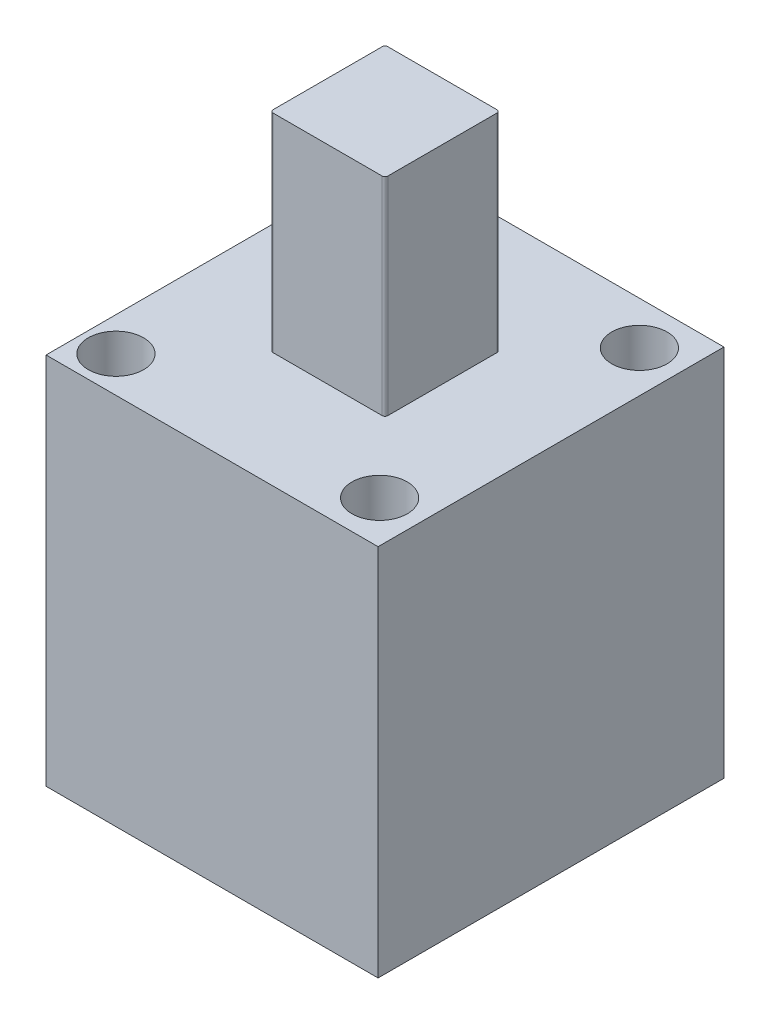
SolidWorks part; units mm, degrees
ref_plane "Alzado" through (0, 0, 0) normal (0, 0, 1) x (1, 0, 0)
ref_plane "Planta" through (0, 0, 0) normal (0, 1, 0) x (1, 0, 0)
ref_plane "Vista lateral" through (0, 0, 0) normal (1, 0, 0) x (0, 0, -1)
sketch "Croquis1" plane through (0, 0, 0) normal (0, 0, 1) x (1, 0, 0)
  line L1 (-49, 13.9228) -> (-25, 13.9228)
  line L2 (-49, 13.9228) -> (-49, -13.0772)
  line L3 (-49, -13.0772) -> (-25, -13.0772)
  line L4 (-25, 13.9228) -> (-25, -13.0772)
  dimension "D1" = 24
  dimension "D2" = 27
extrude "Saliente-Extruir1" add sketch "Croquis1" along normal blind 25
sketch "Croquis2" plane through (0, 13.9228, 0) normal (0, 1, 0) x (1, 0, 0)
  line L0 (-49, 0) -> (-41.15, -8.35) construction
  line L1 (-40.95, -8.35) -> (-33.05, -8.35)
  line L2 (-41.15, -8.55) -> (-41.15, -16.45)
  line L3 (-40.95, -16.65) -> (-33.05, -16.65)
  line L4 (-32.85, -8.55) -> (-32.85, -16.45)
  line L5 (-33.1039, -16.8961) -> (-25, -25) construction
  line L6 (-25, -25) -> (-25, 0) construction
  line L7 (-25, 0) -> (-32.85, -8.35) construction
  line L8 (-41.15, -16.65) -> (-49, -25) construction
  line L11 (-49.9948, -18.9259) -> (-49.9948, -21.9259)
  line L16 (-46.9923, -24.9618) -> (-43.9923, -24.9618)
  circle A0 centre (-45.0661, -4.1845) radius 2
  circle A1 centre (-28.9339, -4.1845) radius 2
  circle A2 centre (-45.0661, -20.8155) radius 2
  circle A3 centre (-28.9233, -21.0767) radius 2
  circle A4 centre (-14.9438, 10.6967) radius 0.6772
  arc A5 (-33.05, -16.65) -> (-32.85, -16.45) centre (-33.05, -16.45) ccw
  arc A6 (-41.15, -16.45) -> (-40.95, -16.65) centre (-40.95, -16.45) ccw
  arc A7 (-33.05, -8.35) -> (-32.85, -8.55) centre (-33.05, -8.55) cw
  arc A8 (-40.95, -8.35) -> (-41.15, -8.55) centre (-40.95, -8.55) ccw
  point P35 (-32.9086, -16.5914)
  dimension "D3" = 0.2
  dimension "D5" = 6
  dimension "D6" = 6
  dimension "D7" = 6
  dimension "D1" = 8.3
  dimension "D2" = 8.3
  dimension "D4" = 6
sketch "Croquis4" plane through (0, 0, 0) normal (0, 0, 1) x (1, 0, 0)
  line L0 (-50, 0) -> (-40.815, -9.185) construction
  line L1 (-40.615, -9.185) -> (-34.385, -9.185)
  line L2 (-40.815, -9.385) -> (-40.815, -15.615)
  line L3 (-40.615, -15.815) -> (-34.385, -15.815)
  line L4 (-34.185, -9.385) -> (-34.185, -15.615)
  line L5 (-34.185, -15.815) -> (-25, -25) construction
  line L6 (-25, -25) -> (-25, 0) construction
  line L7 (-25, 0) -> (-34.185, -9.185) construction
  line L8 (-40.815, -15.815) -> (-50, -25) construction
  circle A0 centre (-44.8576, -5.1424) radius 2
  circle A1 centre (-30.1424, -5.1424) radius 2
  circle A2 centre (-44.8576, -19.8576) radius 2
  circle A3 centre (-30.0009, -19.9991) radius 2
  circle A4 centre (-15.4387, 9.5613) radius 0.6772
  arc A5 (-34.385, -15.815) -> (-34.185, -15.615) centre (-34.385, -15.615) ccw
  arc A6 (-40.815, -15.615) -> (-40.615, -15.815) centre (-40.615, -15.615) ccw
  arc A7 (-34.385, -9.185) -> (-34.185, -9.385) centre (-34.385, -9.385) cw
  arc A8 (-40.615, -9.185) -> (-40.815, -9.385) centre (-40.615, -9.385) ccw
  point P22 (0, 0)
  point P35 (-34.2436, -15.7564)
  dimension "D3" = 0.2
  dimension "D5" = 6
  dimension "D6" = 6
  dimension "D7" = 6
  dimension "D1" = 6.63
  dimension "D2" = 6.63
  dimension "D4" = 6
extrude "Saliente-Extruir2" add sketch "Croquis2" along normal blind 15 contours A8 L1 A7 L4 A5 L3 A6 L2
sketch "Croquis5" plane through (0, 13.9228, 0) normal (0, 1, 0) x (1, 0, 0)
  line L0 (-49, -25) -> (-46.5515, -22.3967) construction
  line L1 (-46.5515, -22.3967) -> (-41.0914, -16.5914) construction
  line L2 (-41.0914, -16.5914) -> (-33.05, -16.65) construction
  line L3 (-33.05, -16.65) -> (-28, -21.8882) construction
  line L4 (-28, -21.8882) -> (-25, -25) construction
  line L5 (-25, -25) -> (-25, 0) construction
  line L6 (-25, -25) -> (-49, -25) construction
  line L7 (-25, -25) -> (-25, 0) construction
  line L8 (-25, 0) -> (-34.185, 0) construction
  line L9 (-25, 0) -> (-28, -3.1118) construction
  line L10 (-28, -3.1118) -> (-33.05, -8.35) construction
  line L11 (-33.05, -8.35) -> (-41.15, -8.55) construction
  line L12 (-41.15, -8.55) -> (-46, -3.2675) construction
  line L13 (-46, -3.2675) -> (-49, 0) construction
  line L25 (-49, -25) -> (-49, 0) construction
  circle A0 centre (-46, -3.2675) radius 2
  circle A1 centre (-28, -3.1118) radius 2
  circle A2 centre (-28, -21.8882) radius 2
  circle A3 centre (-46.5515, -22.3967) radius 2
  arc A4 (-41.15, -16.45) -> (-40.95, -16.65) centre (-40.95, -16.45) ccw construction
  dimension "D1" = 3
  dimension "D2" = 3
  dimension "D3" = 3
extrude "Cortar-Extruir1" cut sketch "Croquis5" against normal blind 27 contours A3 | A2 | A0 | A1
